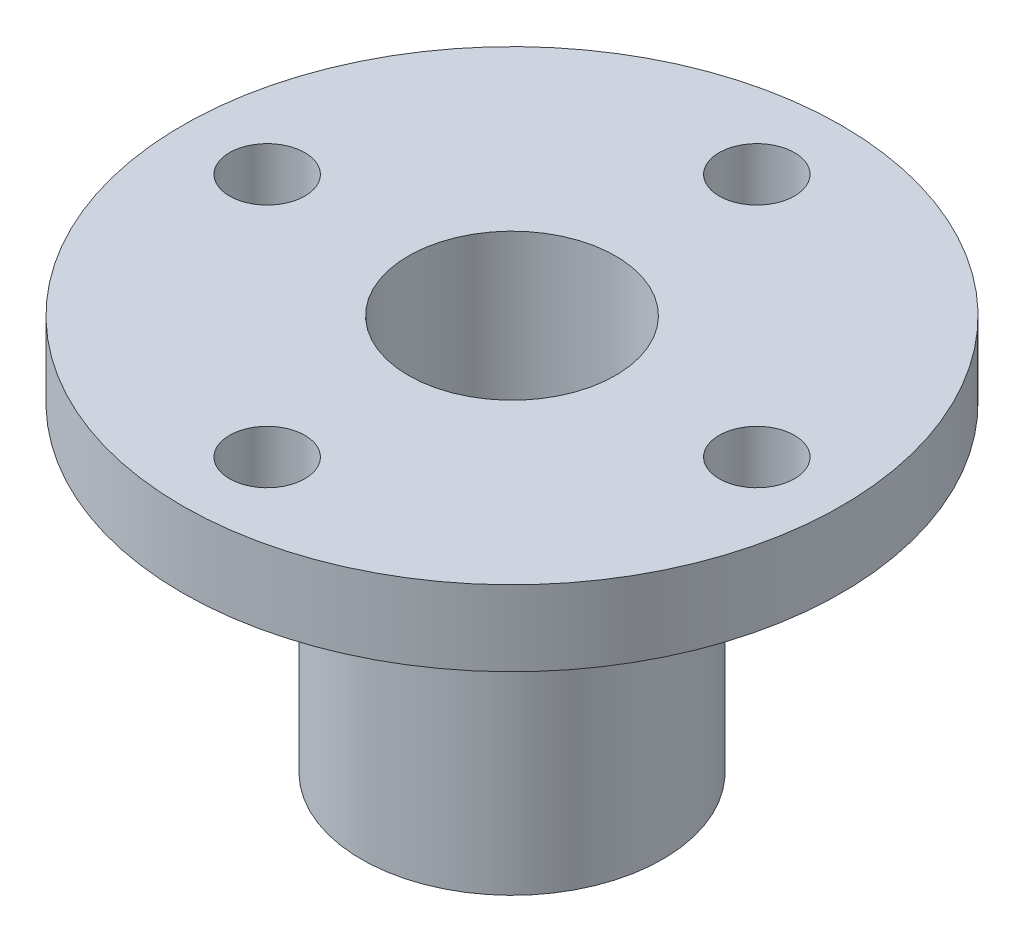
SolidWorks part; units mm, degrees
ref_plane "Front Plane" through (0, 0, 0) normal (0, 0, 1) x (1, 0, 0)
ref_plane "Top Plane" through (0, 0, 0) normal (0, 1, 0) x (1, 0, 0)
ref_plane "Right Plane" through (0, 0, 0) normal (1, 0, 0) x (0, 0, -1)
sketch "Sketch1" plane through (0, 0, 0) normal (0, 1, 0) x (1, 0, 0)
  circle A0 centre (0, 0) radius 17.5
  circle A1 centre (0, 0) radius 13 construction
  circle A2 centre (0, 13) radius 2
  circle A3 centre (0, 0) radius 13 construction
  circle A4 centre (13, 0) radius 2
  circle A5 centre (0, 0) radius 13 construction
  circle A6 centre (0, -13) radius 2
  circle A7 centre (0, 0) radius 13 construction
  circle A8 centre (-13, 0) radius 2
  point P18 (0, 0)
  dimension "D1" = 35
  dimension "D2" = 26
  dimension "D3" = 4
  dimension "D4" = 4
extrude "Boss-Extrude1" add sketch "Sketch1" along normal blind 4
sketch "Sketch2" plane through (0, 0, 0) normal (0, -1, 0) x (1, 0, 0)
  circle A0 centre (0, 0) radius 8
  dimension "D1" = 16
extrude "Boss-Extrude2" add sketch "Sketch2" along normal blind 17
sketch "Sketch3" plane through (0, 4, 0) normal (0, 1, 0) x (1, 0, 0)
  circle A0 centre (0, 0) radius 5.5
  dimension "D1" = 11
extrude "Cut-Extrude1" cut sketch "Sketch3" against normal blind 12
sketch "Sketch4" plane through (0, -8, 0) normal (0, 1, 0) x (1, 0, 0)
  circle A0 centre (0, 0) radius 6
  dimension "D1" = 12
extrude "Cut-Extrude2" cut sketch "Sketch4" against normal blind 1.1
sketch "Sketch5" plane through (0, -9.1, 0) normal (0, 1, 0) x (1, 0, 0)
  circle A0 centre (0, 0) radius 5.5
  dimension "D1" = 11
extrude "Cut-Extrude3" cut sketch "Sketch5" against normal blind 2.9
sketch "Sketch6" plane through (0, -17, 0) normal (0, -1, 0) x (1, 0, 0)
  circle A0 centre (0, 0) radius 2.75
  dimension "D1" = 5.5
extrude "Cut-Extrude4" cut sketch "Sketch6" against normal blind 5.5
